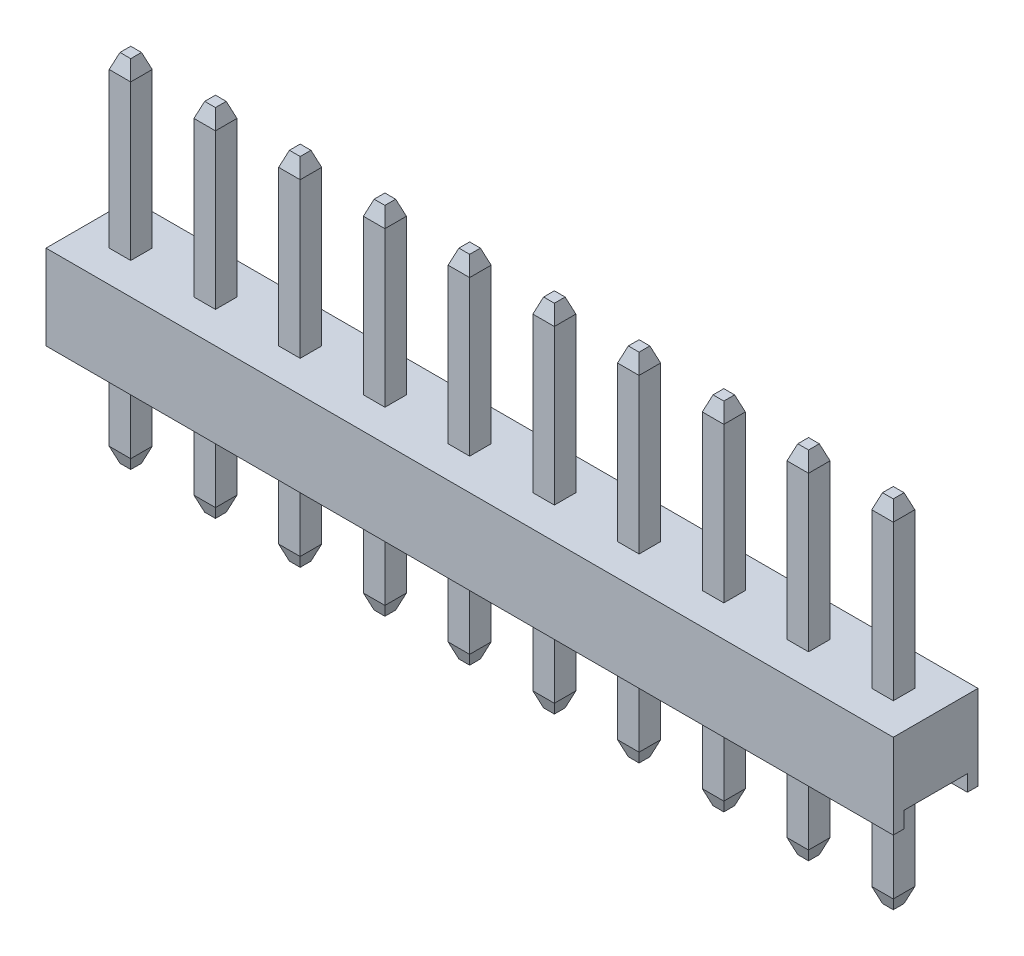
SolidWorks part; units mm, degrees
ref_plane "FRONT" through (0, 0, 0) normal (0, 0, 1) x (1, 0, 0)
ref_plane "TOP" through (0, 0, 0) normal (0, 1, 0) x (1, 0, 0)
ref_plane "RIGHT" through (0, 0, 0) normal (1, 0, 0) x (0, 0, -1)
sketch "Sketch1" plane through (0, 0, 0) normal (1, 0, 0) x (0, 0, -1)
  line L0 (0, 0) -> (0, 23.6894) construction
  line L1 (1, 0.4099) -> (1, 2)
  line L2 (-1, 0) -> (-0.75, 0)
  line L3 (-1, 0) -> (-1, 0.4099)
  line L4 (0.75, 0) -> (0.75, 0.381)
  line L5 (-0.75, 0) -> (-0.75, 0.381)
  line L6 (-0.75, 0.381) -> (0.75, 0.381)
  line L7 (-1, 0.4099) -> (-1, 2)
  line L8 (-1, 2) -> (1, 2)
  line L9 (1, 0) -> (1, 0.4099)
  line L10 (1, 0) -> (0.75, 0)
  point P11 (0, 2)
  point P13 (0, 0.381)
  dimension "D1" = 0.381
  dimension "D2" = 2
  dimension "D3" = 1.5
  dimension "D4" = 2
extrude "Base-Extrude" add sketch "Sketch1" along normal mid plane 20
sketch "Sketch2" plane through (0, 2, 0) normal (0, 1, 0) x (-1, 0, 0)
  line L0 (0, 0) -> (3.254, 0) construction
  line L6 (1.254, -0.254) -> (0.746, -0.254)
  line L7 (1.254, -0.254) -> (1.254, 0.254)
  line L8 (1.254, 0.254) -> (0.746, 0.254)
  line L9 (0.746, -0.254) -> (0.746, 0.254)
  line L10 (1.254, -0.254) -> (0.746, 0.254) construction
  point P2 (1, 0)
  point P3 (0, 0)
  dimension "D1" = 1
  dimension "D2" = 0.508
  dimension "D6" = 0.508
extrude "PINBODY" add sketch "Sketch2" along normal blind 4 and the other way blind 4.4
chamfer "pinsCHAMFER" distance 0.127 angle 70 8 edges at (-1.254, -2.4, 0) (-1, -2.4, 0.254) (-0.746, -2.4, 0) (-1, -2.4, -0.254) (-1.254, 6, 0) (-1, 6, 0.254) (-0.746, 6, 0) (-1, 6, -0.254)
pattern_linear "LPattern1" count 5 spacing 2 along (-1, 0, 0) count 6 spacing 2 along (1, 0, 0) of "PINBODY", "pinsCHAMFER"
